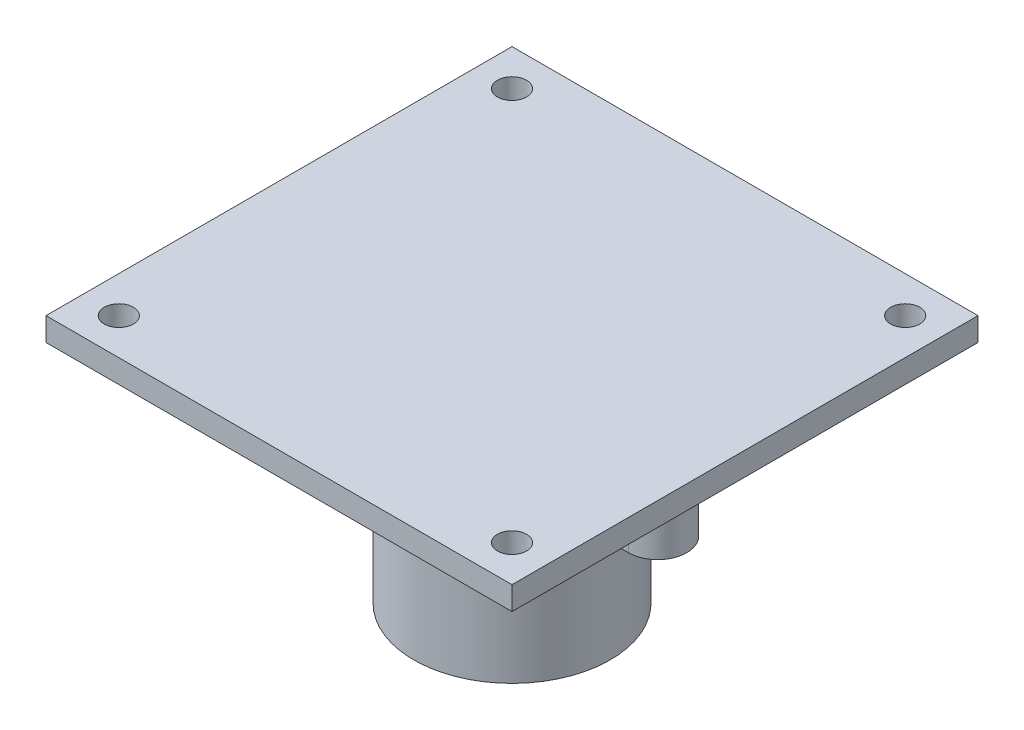
SolidWorks part; units mm, degrees
ref_plane "前视基准面" through (0, 0, 0) normal (0, 0, 1) x (1, 0, 0)
ref_plane "上视基准面" through (0, 0, 0) normal (0, 1, 0) x (1, 0, 0)
ref_plane "右视基准面" through (0, 0, 0) normal (1, 0, 0) x (0, 0, -1)
other "Configuration Table"
sketch "草图1" plane through (0, 0, 0) normal (0, 1, 0) x (1, 0, 0)
  line L1 (-16, -16) -> (16, -16)
  line L2 (-16, -16) -> (-16, 16)
  line L3 (-16, 16) -> (16, 16)
  line L4 (16, -16) -> (16, 16)
  line L5 (-16, -16) -> (16, 16) construction
  line L6 (-16, 16) -> (16, -16) construction
  circle A0 centre (13.5, 13.5) radius 1
  circle A1 centre (-13.5, -13.5) radius 1
  circle A2 centre (-13.5, 13.5) radius 1
  circle A3 centre (13.5, -13.5) radius 1
  point P0 (0, 0)
  dimension "D3" = 27
  dimension "D4" = 27
  dimension "D5" = 2
  dimension "D6" = 2
  dimension "D1" = 32
  dimension "D2" = 32
extrude "凸台-拉伸1" add sketch "草图1" along normal blind 1.6
sketch "草图2" plane through (0, 0, 0) normal (0, -1, 0) x (1, 0, 0)
  line L0 (0, 0) -> (20.6843, 0) construction
  line L1 (-8, -8) -> (8, -8)
  line L2 (-8, -8) -> (-8, 8)
  line L3 (-8, 8) -> (8, 8)
  line L4 (8, -8) -> (8, 8)
  line L5 (-8, -8) -> (8, 8) construction
  line L6 (-8, 8) -> (8, -8) construction
  line L7 (0, 0) -> (0, 13.784) construction
  line L8 (8, 2) -> (10, 2)
  line L9 (8, -2) -> (10, -2)
  line L10 (-8, -2) -> (-10, -2)
  line L11 (-8, 2) -> (-10, 2)
  arc A0 (10, 2) -> (10, -2) centre (10, 0) cw
  arc A1 (-10, 2) -> (-10, -2) centre (-10, 0) ccw
  point P0 (0, 0)
  dimension "D3" = 2
  dimension "D1" = 16
  dimension "D2" = 16
  dimension "D4" = 2
extrude "凸台-拉伸2" add sketch "草图2" along normal blind 6.5 contours L1 L4 L3 L2 | L11 A1 L10 L2 | A0 L8 L4 L9
sketch "草图3" plane through (0, -6.5, 0) normal (0, -1, 0) x (1, 0, 0)
  circle A0 centre (0, 0) radius 6.75
  dimension "D1" = 13.5
extrude "凸台-拉伸3" add sketch "草图3" along normal blind 9
